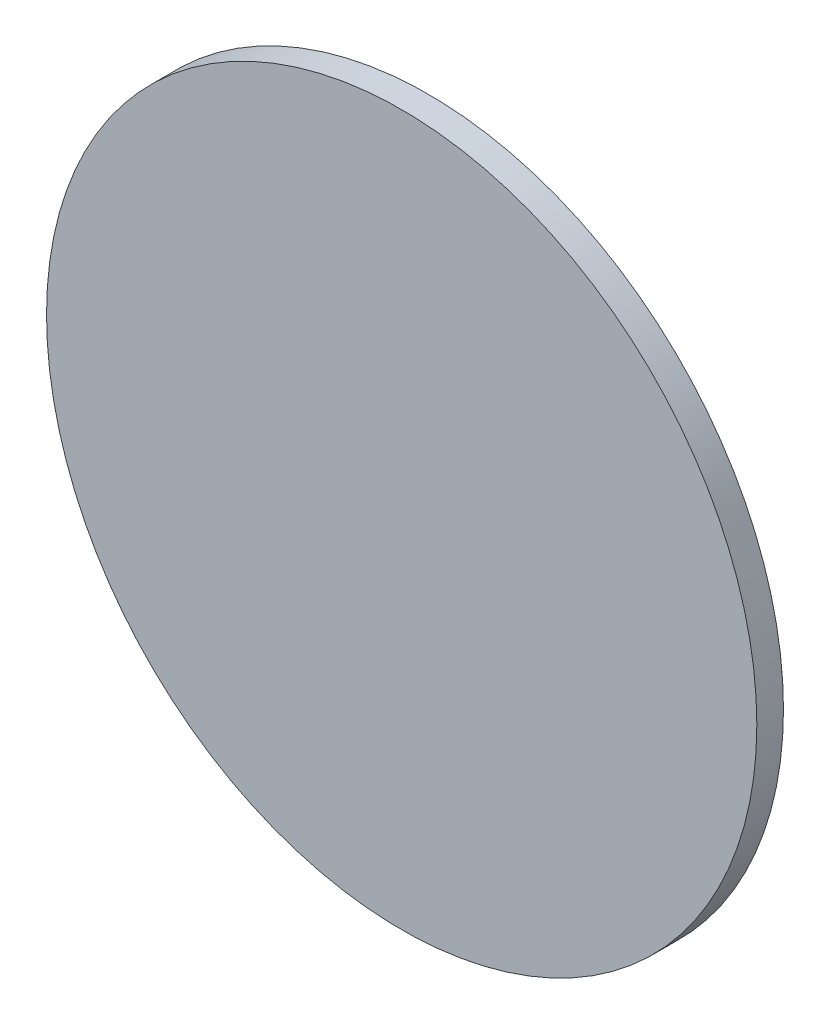
SolidWorks part; units mm, degrees
ref_plane "Front Plane" through (0, 0, 0) normal (0, 0, 1) x (1, 0, 0)
ref_plane "Top Plane" through (0, 0, 0) normal (0, 1, 0) x (1, 0, 0)
ref_plane "Right Plane" through (0, 0, 0) normal (1, 0, 0) x (0, 0, -1)
sketch "Sketch1" plane through (0, 0, 0) normal (0, 0, 1) x (1, 0, 0)
  circle A0 centre (0, 0) radius 50.8
  dimension "D1" = 101.6
extrude "Boss-Extrude1" add sketch "Sketch1" along normal blind 3.81
equation "\"D1@Boss-Extrude1\"=0.15"
